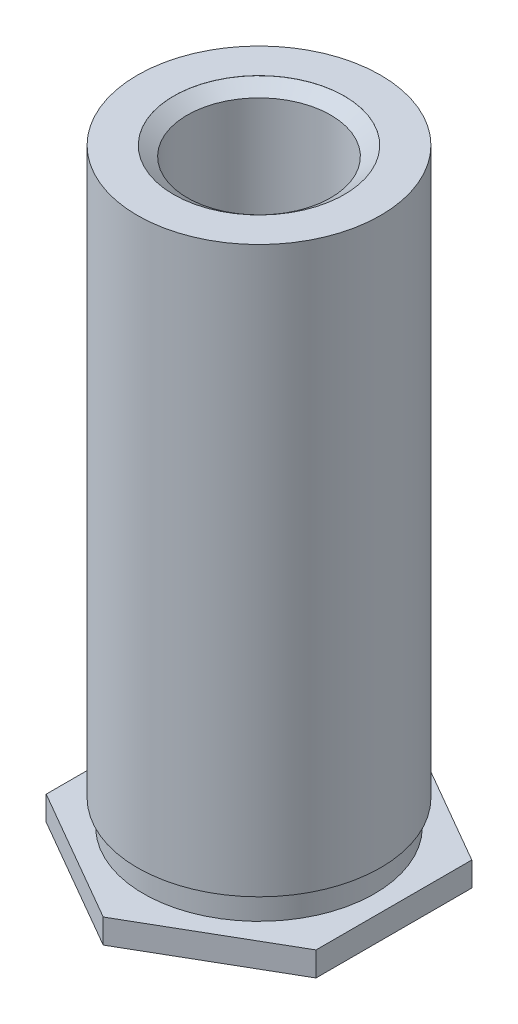
SolidWorks part; units mm, degrees
revolve "Body" add sketch "BodySke"
sketch "BodySke" plane through (0, 0, 0) normal (0, 0, 1) x (1, 0, 0)
  line L0 (3.56, 0) -> (4.582, 0)
  line L1 (4.582, 0) -> (4.582, 0.712)
  line L2 (4.582, 0.712) -> (3.382, 0.712)
  line L3 (2.1, 18) -> (2.1, 8.5)
  line L4 (3.56, 1.4596) -> (3.382, 1.4596)
  line L5 (3.382, 1.4596) -> (3.382, 0.712)
  line L6 (3.56, 0.0025) -> (3.56, 0)
  line L7 (1.016, 17.2) -> (3.6522, 17.2) construction
  line L8 (3.56, 18) -> (2.1, 18)
  line L9 (0, 0) -> (0, 15.24) construction
  line L10 (3.56, 0.0025) -> (0, 0.0025)
  line L11 (3.56, 18) -> (3.56, 1.4596)
  line L12 (0, 8.5) -> (2.1, 8.5)
  line L13 (0, 8.5) -> (0, 0.0025)
  line L14 (1.016, 8.5) -> (3.6522, 8.5) construction
  line L15 (1.016, 8.5) -> (3.6522, 8.5) construction
  dimension "E_dia" = 9.164
  dimension "Thread_min" = 4.2
  dimension "C_dia" = 7.12
  dimension "Thread_limit" = 9.5
  dimension "Advance" = 0.8
  dimension "Thread_depth" = 9.5
  dimension "Drill_depth" = 9.5
  dimension "Length" = 18
  dimension "Clinching_ht" = 0.712
  dimension "Groove_wid" = 0.7476
  dimension "Groove_dia" = 6.764
  dimension "D1" = 0.0025
cosmetic thread "ThreadCosmetic" [suppressed]
revolve "EndChamfer" cut sketch "EndChamferSke" angle 360 about L0
sketch "EndChamferSke" plane through (0, 0, 0) normal (0, 0, 1) x (1, 0, 0)
  line L0 (0, -2.54) -> (0, 7.62) construction
  line L1 (0, 0) -> (0, 15.24) construction
  line L6 (2.5, 17.9975) -> (2.1, 17.7175)
  line L7 (2.5, 17.9975) -> (2.5, 18.254)
  line L8 (2.1, 17.7175) -> (2.1, 18.254)
  line L9 (2.5, 18.254) -> (2.1, 18.254)
  line L10 (3.56, 18) -> (-3.56, 18) construction
  dimension "D1" = 0.254
  dimension "Thread_nominal" = 5
  dimension "D2" = 34.99
  dimension "Thread_min" = 4.2
  dimension "Inset" = 0.0025
revolve "TapDrill" cut sketch "TapDriSke" angle 360 about L0
sketch "TapDriSke" plane through (0, 0, 0) normal (0, 0, 1) x (1, 0, 0)
  line L0 (0, 0) -> (0, 15.24) construction
  line L1 (0, 0) -> (0, 15.24) construction
  line L2 (2.1, 4.5) -> (2.1, 18)
  line L3 (3.56, 18) -> (-3.56, 18) construction
  line L4 (2.1, 4.5) -> (0, 3.6302)
  line L5 (0, 3.6302) -> (0, 18)
  line L6 (0, 18) -> (2.1, 18)
  line L7 (2.1, 8.5) -> (2.1, 18) construction
  line L8 (0, 3.6302) -> (-2.1, 4.5) construction
  line L9 (-2.1, 18) -> (-2.1, 8.5) construction
  line L10 (0, 1.4596) -> (4.826, 1.4596) construction
  dimension "D1" = 135
ref_plane "Plane1" through (0, 0, 0) normal (0, 0, 1) x (1, 0, 0)
ref_plane "Plane2" through (0, 0, 0) normal (0, 1, 0) x (1, 0, 0)
ref_plane "Plane3" through (0, 0, 0) normal (1, 0, 0) x (0, 0, -1)
ref_plane "Plane4" through (0, -0.5486, 0) normal (0, 1, 0) x (-1, 0, 0)
sketch "ThdSchSke" plane through (0, 0, 0) normal (0, 0, 1) x (1, 0, 0)
  line L0 (0, -5.08) -> (0, 7.62) construction
  line L1 (0, 0) -> (0, 15.24) construction
  line L2 (0, 17.9975) -> (2.5, 17.9975) construction
  line L3 (2.5, 17.9975) -> (-2.5, 17.9975) construction
  line L4 (2.5, 17.9975) -> (2.1, 18.2775)
  line L6 (2.5, 17.9975) -> (2.1, 17.7174)
  line L7 (2.1, 18.2775) -> (2.1, 17.7174)
  dimension "Thread_min" = 4.2
revolve "ThreadSchematic" [suppressed] cut sketch "ThdSchSke" angle 360 about L0
pattern_linear "ThdSchPat" [suppressed]
sketch "HexDieSke" plane through (0, 0.712, 0) normal (0, 1, 0) x (-1, 0, 0)
  line L0 (0, 4.5611) -> (3.95, 2.2805)
  line L1 (3.95, 2.2805) -> (3.95, -2.2805)
  line L2 (3.95, -2.2805) -> (0, -4.5611)
  line L3 (0, -4.5611) -> (-3.95, -2.2805)
  line L4 (-3.95, -2.2805) -> (-3.95, 2.2805)
  line L5 (-3.95, 2.2805) -> (0, 4.5611)
  circle A1 centre (0, 0) radius 3.95 construction
  circle A2 centre (0, 0) radius 4.5611 construction
  circle A3 centre (0, 0) radius 4.5825
  dimension "Width_across_flats" = 7.9
  dimension "OD" = 9.165
extrude "HexDie" cut sketch "HexDieSke" against normal blind 0.712
equation "' \"Length@BodySke\" = 18"
equation "' \"C_dia@BodySke\" = 7.12"
equation "' \"Width_across_flats@HexDieSke\" = 7.9"
equation "' \"Thread_depth@BodySke\" = 9.5"
equation "' \"Advance@BodySke\" = 0.8"
equation "' \"Thread_min@BodySke\" = 4.2"
equation "' \"Thread_nominal@ThreadCosmetic\" = 5"
equation "\"E_dia@BodySke\" = \"Width_across_flats@HexDieSke\" * 1.16"
equation "\"Clinching_ht@BodySke\" = \"C_dia@BodySke\" * 0.1"
equation "\"Groove_dia@BodySke\" = \"C_dia@BodySke\" * 0.95"
equation "\"Groove_wid@BodySke\" = \"Clinching_ht@BodySke\" * 1.05"
equation "\"Drill_depth@BodySke\" = \"Thread_depth@BodySke\""
equation "\"Drill_limit@TapDriSke\" = \"Length@BodySke\" - \"Clinching_ht@BodySke\" - \"Groove_wid@BodySke\""
equation "\"Thread_limit@BodySke\" = ((sgn( \"Length@BodySke\" - \"Thread_depth@BodySke\" )-1)*( \"Length@BodySke\" - \"Thread_depth@BodySke\" ))/-2+ \"Thread_depth@BodySke\""
equation "\"Depth@TapDriSke\" = \"Thread_limit@BodySke\" + \"Advance@BodySke\" * 5"
equation "\"Depth@TapDriSke\" = ((sgn( \"Depth@TapDriSke\" - \"Drill_limit@TapDriSke\" )-1)*( \"Depth@TapDriSke\" - \"Drill_limit@TapDriSke\" ))/-2+ \"Drill_limit@TapDriSke\""
equation "\"Depth@HexDie\" = \"Clinching_ht@BodySke\""
equation "\"OD@HexDieSke\" =  \"Width_across_flats@HexDieSke\" * 1.16 + 0.001"
equation "\"Thread_nominal@EndChamferSke\" = \"Thread_nominal@ThreadCosmetic\""
equation "\"Thread_min@EndChamferSke\" = \"Thread_min@BodySke\""
equation "\"D2@EndChamferSke\" = \"Vee_angle@ThdSchSke\" / 2 - 0.01"
equation "\"Thread_nominal@ThdSchSke\" = \"Thread_nominal@ThreadCosmetic\""
equation "\"Thread_min@ThdSchSke\" = \"Thread_min@BodySke\""
equation "\"Num_threads@ThdSchPat\" = int(  ( \"Thread_limit@BodySke\" - \"Inset@EndChamferSke\" ) / \"Advance@BodySke\" + 0.999 )  + 1"
equation "\"Advance@ThdSchPat\" = (  \"Thread_limit@BodySke\" - \"Inset@EndChamferSke\" ) /  (\"Num_threads@ThdSchPat\" - 1) 'relax it"
